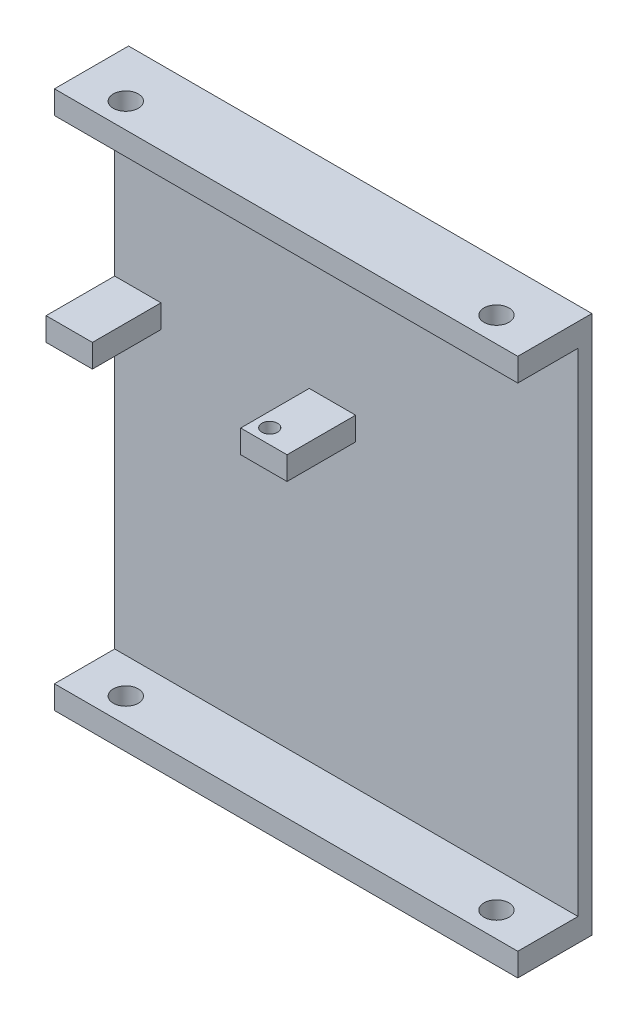
SolidWorks part; units mm, degrees
ref_plane "Front Plane" through (0, 0, 0) normal (0, 0, 1) x (1, 0, 0)
ref_plane "Top Plane" through (0, 0, 0) normal (0, 1, 0) x (1, 0, 0)
ref_plane "Right Plane" through (0, 0, 0) normal (1, 0, 0) x (0, 0, -1)
sketch "Sketch1" plane through (0, 0, 0) normal (0, 0, 1) x (1, 0, 0)
  line L1 (0, 0) -> (127, 0)
  line L2 (0, 0) -> (0, 147.574)
  line L3 (0, 147.574) -> (127, 147.574)
  line L4 (127, 0) -> (127, 147.574)
  dimension "D1" = 127
  dimension "D2" = 147.574
extrude "Boss-Extrude1" add sketch "Sketch1" along normal blind 3.81
sketch "Sketch3" plane through (0, 0, 3.81) normal (0, 0, 1) x (1, 0, 0)
  line L0 (127, 0) -> (127, 147.574) construction
  line L1 (0, 147.574) -> (127, 147.574)
  line L2 (0, 147.574) -> (0, 141.224)
  line L3 (0, 141.224) -> (127, 141.224)
  line L4 (127, 147.574) -> (127, 141.224)
  line L6 (0, 0) -> (127, 0)
  line L7 (0, 0) -> (0, 6.35)
  line L8 (0, 6.35) -> (127, 6.35)
  line L9 (127, 0) -> (127, 6.35)
  dimension "D1" = 6.35
  dimension "D2" = 6.35
extrude "Boss-Extrude2" add sketch "Sketch3" along normal blind 16.51
sketch "Sketch4" plane through (0, 0, 0) normal (0, -1, 0) x (1, 0, 0)
  line L0 (0, 20.32) -> (127, 20.32) construction
  line L1 (127, 20.32) -> (127, 0) construction
  circle A0 centre (12.7, 13.462) radius 3.429
  circle A1 centre (114.3, 13.462) radius 3.429
  dimension "D2" = 6.858
  dimension "D3" = 6.858
  dimension "D4" = 6.858
  dimension "D6" = 6.858
  dimension "D1" = 101.6
  dimension "D5" = 12.7
extrude "Cut-Extrude1" cut sketch "Sketch4" against normal through all
sketch "Sketch6" plane through (0, 0, 3.81) normal (0, 0, 1) x (1, 0, 0)
  line L0 (0, 141.224) -> (127, 141.224) construction
  line L1 (0, 88.519) -> (12.7, 88.519)
  line L2 (0, 73.787) -> (25.6558, 73.787) construction
  line L3 (0, 88.519) -> (12.7, 88.519) construction
  line L4 (0, 88.519) -> (0, 94.869)
  line L5 (0, 94.869) -> (12.7, 94.869)
  line L6 (12.7, 88.519) -> (12.7, 94.869)
  line L7 (53.34, 88.519) -> (66.04, 88.519)
  line L8 (53.34, 88.519) -> (53.34, 94.869)
  line L9 (53.34, 94.869) -> (66.04, 94.869)
  line L10 (66.04, 88.519) -> (66.04, 94.869)
  line L12 (0, 141.224) -> (0, 6.35) construction
  point P2 (53.34, 91.694)
  point P13 (63.5, 141.224)
  dimension "D1" = 14.732
  dimension "D2" = 6.35
  dimension "D3" = 12.7
  dimension "D4" = 6.35
  dimension "D5" = 12.7
  dimension "D6" = 40.64
  dimension "D7" = 46.355
  dimension "D8" = 46.355
  dimension "D9" = 0
extrude "Boss-Extrude3" add sketch "Sketch6" along normal blind 18.796
sketch "Sketch9" plane through (0, 88.519, 0) normal (0, -1, 0) x (-1, 0, 0)
  line L0 (-6.35, -22.606) -> (-6.35, -3.81) construction
  line L1 (0, -22.606) -> (-12.7, -22.606) construction
  line L2 (0, -3.81) -> (-12.7, -3.81) construction
  line L3 (-6.35, -3.81) -> (-12.7, -3.81) construction
  line L4 (-59.69, -22.606) -> (-59.69, -3.81) construction
  line L5 (-53.34, -22.606) -> (-66.04, -22.606) construction
  line L6 (-53.34, -3.81) -> (-66.04, -3.81) construction
  line L7 (-59.69, -3.81) -> (-53.34, -3.81) construction
  line L8 (-8.636, -22.606) -> (-8.636, -3.81) construction
  line L9 (-57.404, -22.606) -> (-57.404, -3.81) construction
  line L10 (-53.34, -22.606) -> (-53.34, -3.81) construction
  line L11 (-12.7, -22.606) -> (-12.7, -3.81) construction
  circle A0 centre (-8.636, -18.034) radius 2.032
  circle A2 centre (-8.636, -8.382) radius 2.032
  circle A3 centre (-57.404, -8.382) radius 2.032
  arc A5 (-59.2, -19.46) -> (-59.2, -17.66) centre (-57.2474, -18.56) ccw construction
  arc A6 (-59.2, -19.46) -> (-59.2, -17.66) centre (-57.2474, -18.56) ccw construction
  circle A7 centre (-57.2474, -18.56) radius 4.0108
  dimension "D3" = 4.064
  dimension "D4" = 4.064
  dimension "D6" = 4.064
  dimension "D1" = 4.064
  dimension "D2" = 4.064
  dimension "D7" = 9.652
  dimension "D9" = 4.572
  dimension "D10" = 4.572
extrude "Cut-Extrude3" [suppressed] cut sketch "Sketch9" against normal up to surface (6.35 mm away)
sketch "Sketch10" plane through (0, 88.519, 0) normal (0, -1, 0) x (1, 0, 0)
  arc A0 (59.2, 19.46) -> (59.2, 17.66) centre (57.2474, 18.56) ccw construction
  arc A1 (59.217, 19.4223) -> (59.2, 17.66) centre (57.2474, 18.56) ccw
  arc A2 (59.2, 17.66) -> (59.2, 19.46) centre (57.2474, 18.56) ccw
  point P4 (59.217, 19.4223)
extrude "Cut-Extrude4" cut sketch "Sketch10" against normal up to surface (6.35 mm away) contours A1 A2 up to face at (59.69, 94.869, 13.208)
